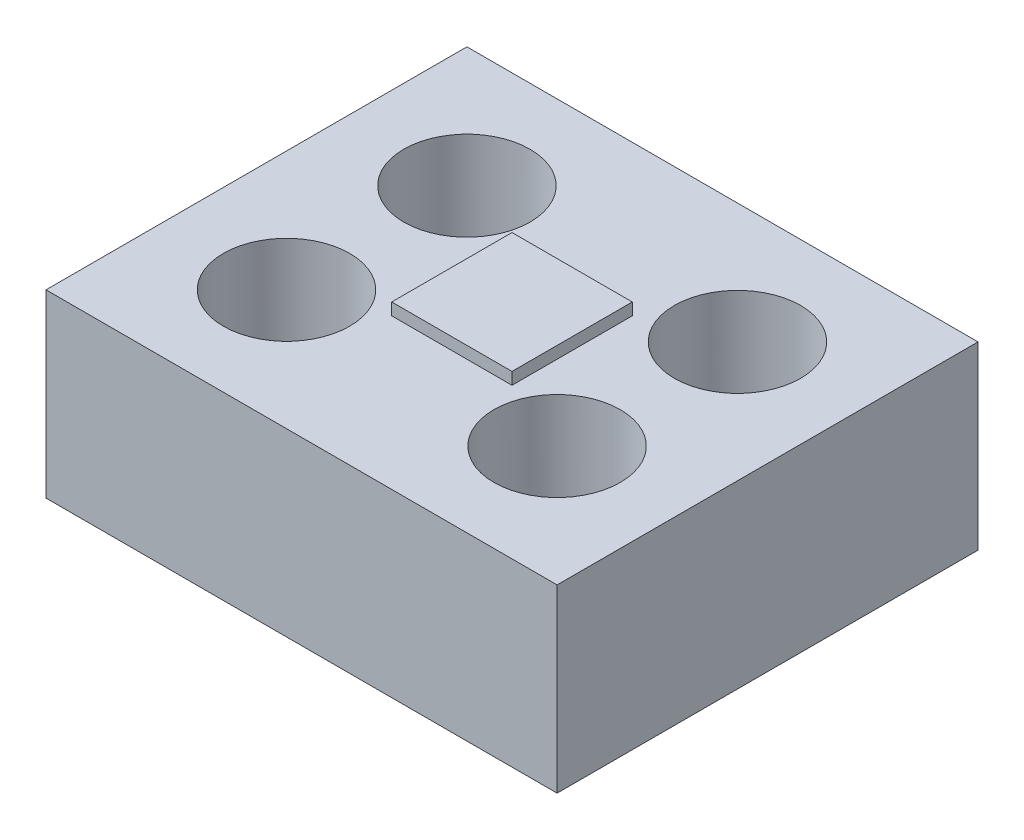
SolidWorks part; units mm, degrees
ref_plane "Front Plane" through (0, 0, 0) normal (0, 0, 1) x (1, 0, 0)
ref_plane "Top Plane" through (0, 0, 0) normal (0, 1, 0) x (1, 0, 0)
ref_plane "Right Plane" through (0, 0, 0) normal (1, 0, 0) x (0, 0, -1)
sketch "Sketch1" plane through (0, 0, 0) normal (0, 1, 0) x (1, 0, 0)
  line L0 (-225, 150) -> (225, 150) construction
  line L1 (225, 150) -> (225, -150) construction
  line L2 (225, -150) -> (-225, -150) construction
  line L3 (-225, -150) -> (-225, 150) construction
  line L4 (0, 150) -> (0, -150) construction
  line L5 (-225, 0) -> (225, 0) construction
  line L7 (-425, 350) -> (425, 350)
  line L8 (-425, 350) -> (-425, -350)
  line L9 (-425, -350) -> (425, -350)
  line L10 (425, 350) -> (425, -350)
  circle A0 centre (-225, 150) radius 105
  circle A1 centre (225, 150) radius 105
  circle A2 centre (-225, -150) radius 105
  circle A3 centre (225, -150) radius 105
  spline S0 degree 1 poles (-225, 30.9288) (-425, 37.2683) knots 0 0 1 1
  dimension "D1" = 210
  dimension "D2" = 150
  dimension "D3" = 450
  dimension "D4" = 200
  dimension "D5" = 200
  dimension "D6" = 200
  dimension "D7" = 200
extrude "Boss-Extrude1" add sketch "Sketch1" along normal blind 300 contours L8 L7 L10 L9 | A2 | A0 | A1 | A3
sketch "Sketch2" plane through (0, 0, 0) normal (0, -1, 0) x (1, 0, 0)
  line L1 (-355.4773, 298.4974) -> (363.2473, 298.4974)
  line L2 (-355.4773, 298.4974) -> (-355.4773, -308.8574)
  line L3 (-355.4773, -308.8574) -> (363.2473, -308.8574)
  line L4 (363.2473, 298.4974) -> (363.2473, -308.8574)
extrude "Boss-Extrude2" add sketch "Sketch2" against normal blind 100
sketch "Sketch3" plane through (0, 100, 0) normal (0, 1, 0) x (1, 0, 0)
  circle A0 centre (-225, 150) radius 30
  circle A1 centre (-225, -150) radius 105 construction
  circle A2 centre (-225, -150) radius 105
  circle A3 centre (225, 150) radius 105 construction
  circle A4 centre (225, 150) radius 105
  circle A5 centre (-225, 150) radius 105 construction
  circle A6 centre (-225, 150) radius 105
  circle A7 centre (225, -150) radius 105 construction
  circle A8 centre (225, -150) radius 105
  circle A9 centre (225, 150) radius 30
  circle A10 centre (225, -150) radius 30
  circle A11 centre (-225, -150) radius 30
  dimension "D1" = 60
extrude "Boss-Extrude3" add sketch "Sketch3" along normal blind 10 contours A9 | A0 | A11 | A10
sketch "Sketch4" plane through (-425, 0, 0) normal (-1, 0, 0) x (0, 0, 1)
  line L0 (0, 300) -> (0, 0) construction
  line L1 (-350, 300) -> (350, 300) construction
  circle A0 centre (0, 150) radius 141
  dimension "D1" = 282
extrude "Cut-Extrude1" cut sketch "Sketch4" against normal blind 200 from offset 325 offset against normal yes
sketch "Sketch5" plane through (100, 0, 0) normal (-1, 0, 0) x (0, 0, 1)
  circle A0 centre (0, 150) radius 141 construction
  circle A1 centre (0, 150) radius 141
  circle A2 centre (0, 150) radius 50
  dimension "D1" = 100
extrude "Cut-Extrude2" cut sketch "Sketch5" against normal blind 20 and the other way blind 220 contours A2
sketch "Sketch6" plane through (0, 300, 0) normal (0, 1, 0) x (1, 0, 0)
  line L1 (-100, 100) -> (100, 100)
  line L2 (-100, 100) -> (-100, -100)
  line L3 (-100, -100) -> (100, -100)
  line L4 (100, 100) -> (100, -100)
  dimension "D1" = 100
  dimension "D2" = 100
  dimension "D3" = 100
  dimension "D4" = 100
extrude "Boss-Extrude4" add sketch "Sketch6" along normal blind 20
